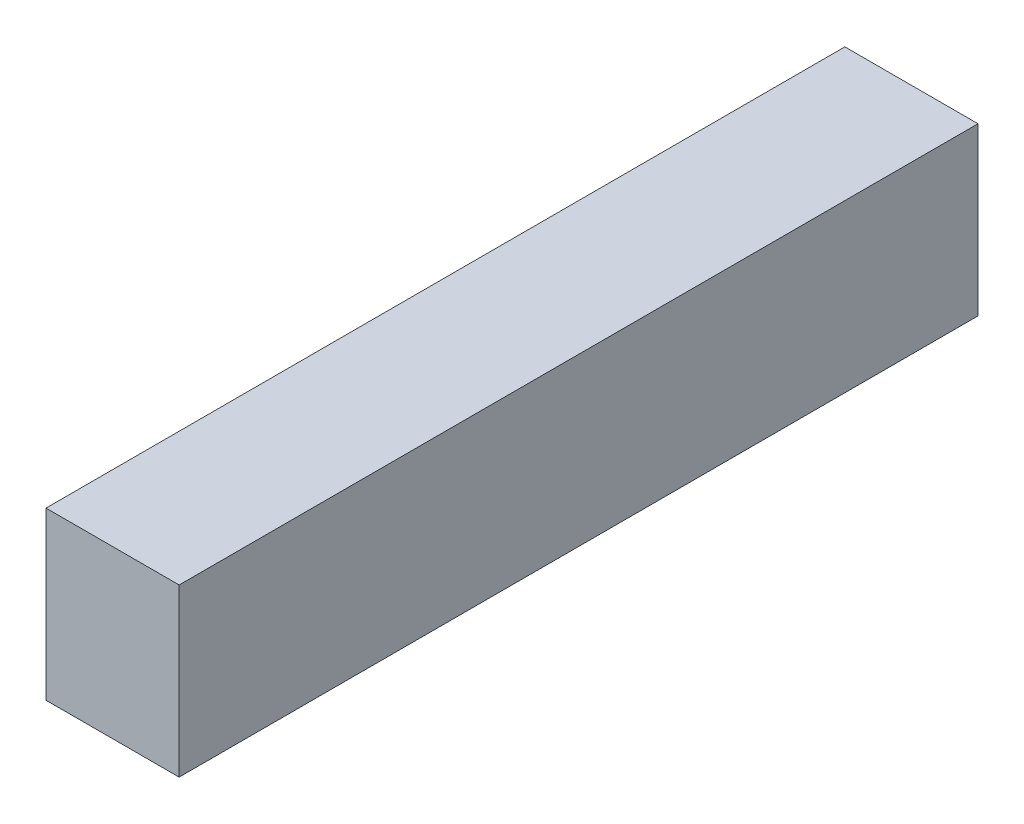
SolidWorks part; units mm, degrees
ref_plane "Front Plane" through (0, 0, 0) normal (0, 0, 1) x (1, 0, 0)
ref_plane "Top Plane" through (0, 0, 0) normal (0, 1, 0) x (1, 0, 0)
ref_plane "Right Plane" through (0, 0, 0) normal (1, 0, 0) x (0, 0, -1)
sketch "Sketch1" plane through (0, 0, 0) normal (0, 1, 0) x (1, 0, 0)
  line L1 (-4, -24) -> (4, -24)
  line L2 (-4, -24) -> (-4, 24)
  line L3 (-4, 24) -> (4, 24)
  line L4 (4, -24) -> (4, 24)
  line L5 (-4, -24) -> (4, 24) construction
  line L6 (-4, 24) -> (4, -24) construction
  point P0 (0, 0)
  dimension "D1" = 8
  dimension "D2" = 48
extrude "Boss-Extrude1" add sketch "Sketch1" against normal blind 10
